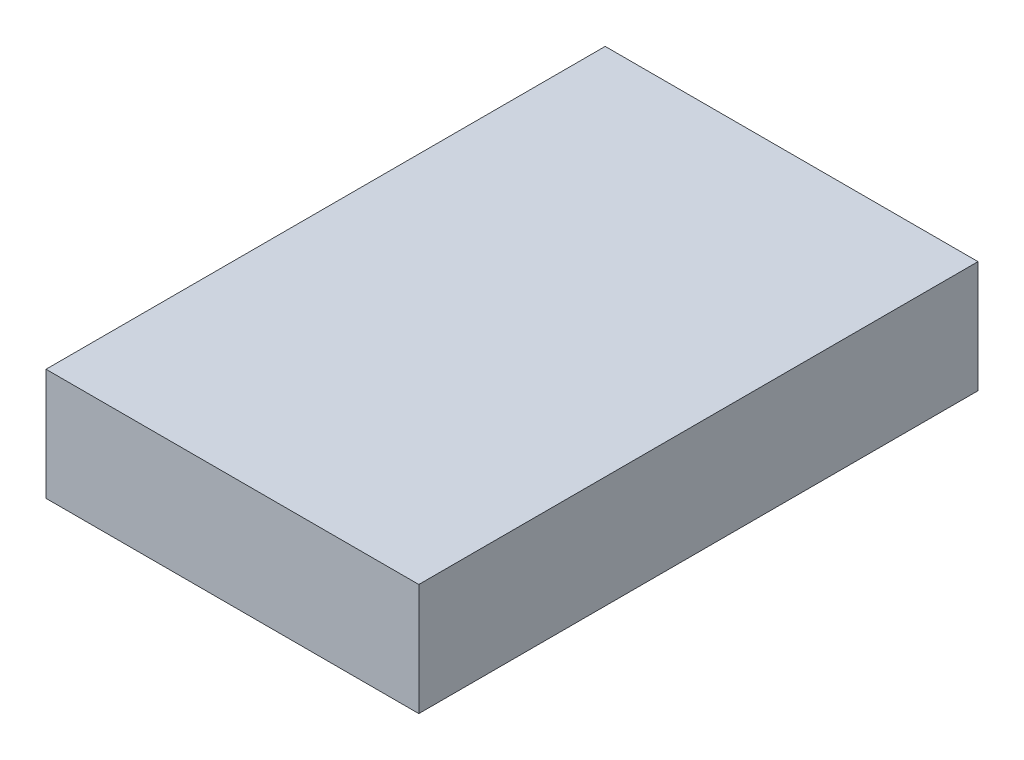
SolidWorks part; units mm, degrees
ref_plane "Front Plane" through (0, 0, 0) normal (0, 0, 1) x (1, 0, 0)
ref_plane "Top Plane" through (0, 0, 0) normal (0, 1, 0) x (1, 0, 0)
ref_plane "Right Plane" through (0, 0, 0) normal (1, 0, 0) x (0, 0, -1)
sketch "Sketch1" plane through (0, 0, 0) normal (0, 0, 1) x (1, 0, 0)
  line L1 (-10, 3) -> (10, 3)
  line L2 (-10, 3) -> (-10, -3)
  line L3 (-10, -3) -> (10, -3)
  line L4 (10, 3) -> (10, -3)
  line L5 (-10, 3) -> (10, -3) construction
  line L6 (-10, -3) -> (10, 3) construction
  point P0 (0, 0)
  dimension "D1" = 20
  dimension "D2" = 6
extrude "Boss-Extrude1" add sketch "Sketch1" along normal mid plane 30
